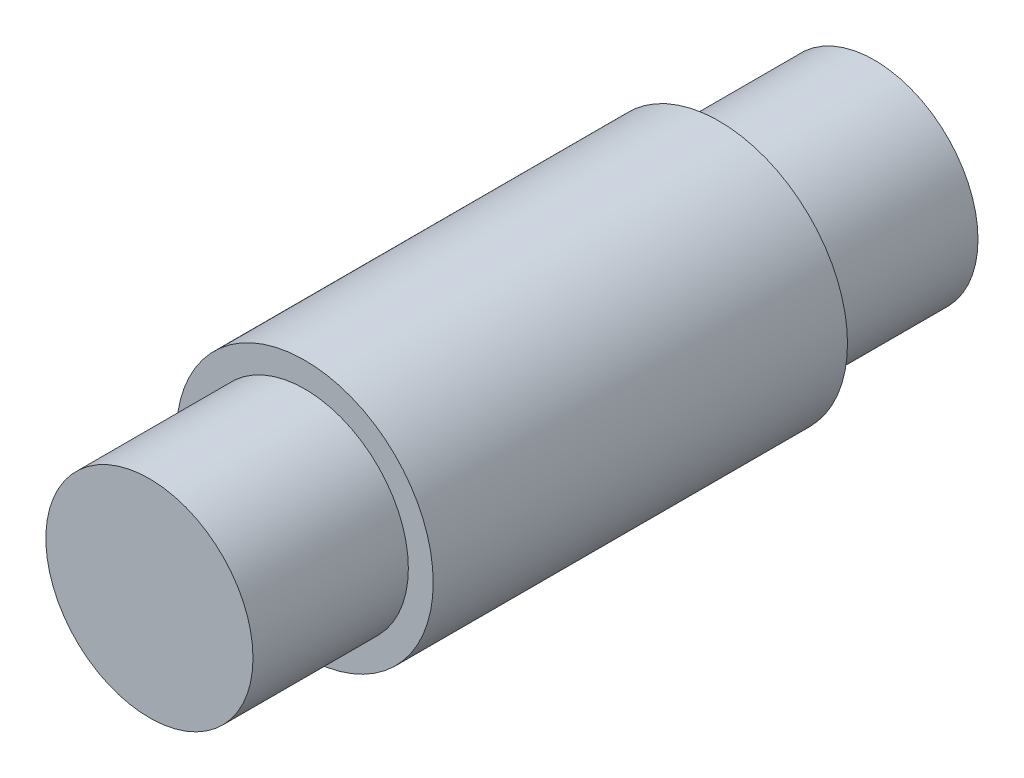
SolidWorks part; units mm, degrees
ref_plane "Front Plane" through (0, 0, 0) normal (0, 0, 1) x (1, 0, 0)
ref_plane "Top Plane" through (0, 0, 0) normal (0, 1, 0) x (1, 0, 0)
ref_plane "Right Plane" through (0, 0, 0) normal (1, 0, 0) x (0, 0, -1)
sketch "Sketch1" plane through (0, 0, 0) normal (0, 1, 0) x (1, 0, 0)
  line L0 (0, 0) -> (0, -4.7625)
  line L1 (0, -4.7625) -> (0.762, -4.7625)
  line L2 (0.762, -4.7625) -> (0.762, -17.4625)
  line L3 (0.762, -17.4625) -> (0, -17.4625)
  line L4 (0, -17.4625) -> (0, -22.225)
  line L5 (0, -22.225) -> (-3.175, -22.225)
  line L6 (-3.175, -22.225) -> (-3.175, 0)
  line L7 (-3.175, 0) -> (0, 0)
  dimension "D1" = 4.7625
  dimension "D2" = 12.7
  dimension "D3" = 3.937
  dimension "D4" = 3.175
revolve "Revolve1" add sketch "Sketch1" angle 360 about L6
